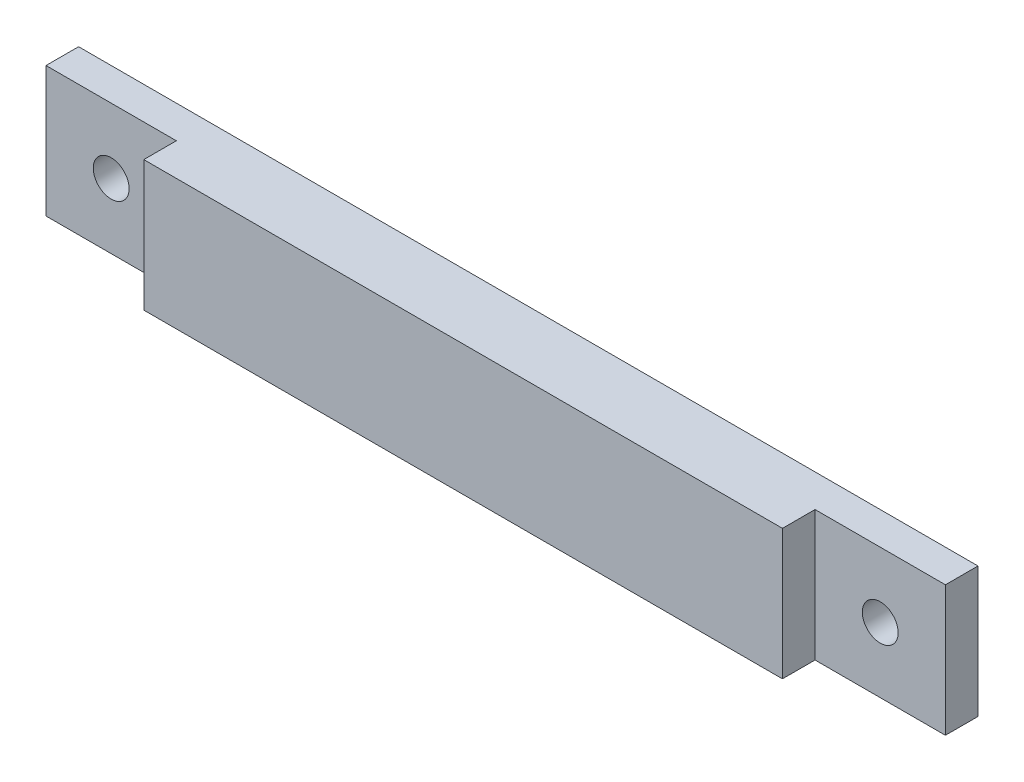
SolidWorks part; units mm, degrees
ref_plane "Plan de face" through (0, 0, 0) normal (0, 0, 1) x (1, 0, 0)
ref_plane "Plan de dessus" through (0, 0, 0) normal (0, 1, 0) x (1, 0, 0)
ref_plane "Plan de droite" through (0, 0, 0) normal (1, 0, 0) x (0, 0, -1)
sketch "Esquisse1" plane through (0, 0, 0) normal (0, 0, 1) x (1, 0, 0)
  line L0 (137.985, 40) -> (137.985, 0) construction
  line L2 (0, 0) -> (0, 40)
  line L3 (0, 40) -> (275.97, 40)
  line L4 (275.97, 0) -> (275.97, 40)
  line L5 (0, 0) -> (275.97, 0)
  circle A0 centre (20, 20) radius 5.5
  circle A1 centre (255.97, 20) radius 5.5
  point P11 (137.985, 0)
  dimension "D5" = 11
  dimension "D1" = 275.97
  dimension "D2" = 40
  dimension "D3" = 20
  dimension "D4" = 20
extrude "Boss.-Extru.1" add sketch "Esquisse1" along normal blind 10
sketch "Esquisse2" plane through (0, 0, 10) normal (0, 0, 1) x (1, 0, 0)
  line L0 (0, 0) -> (275.97, 0) construction
  line L1 (40, 0) -> (235.97, 0)
  line L2 (40, 0) -> (40, 40)
  line L3 (40, 40) -> (235.97, 40)
  line L4 (235.97, 0) -> (235.97, 40)
  line L5 (275.97, 40) -> (0, 40) construction
  line L6 (40, 40) -> (235.97, 40)
  line L7 (235.97, 0) -> (40, 0)
  circle A0 centre (20, 20) radius 5.5 construction
  circle A1 centre (255.97, 20) radius 5.5 construction
  line M4 (0, 0) -> (275.97, 0)
  line M6 (275.97, 40) -> (0, 40)
  dimension "D1" = 20
  dimension "D2" = 20
extrude "Boss.-Extru.2" add sketch "Esquisse2" along normal blind 10 contours L4 L2 M4 M6
equation "\"D2@Esquisse2\"=\"D1@Esquisse2\""
